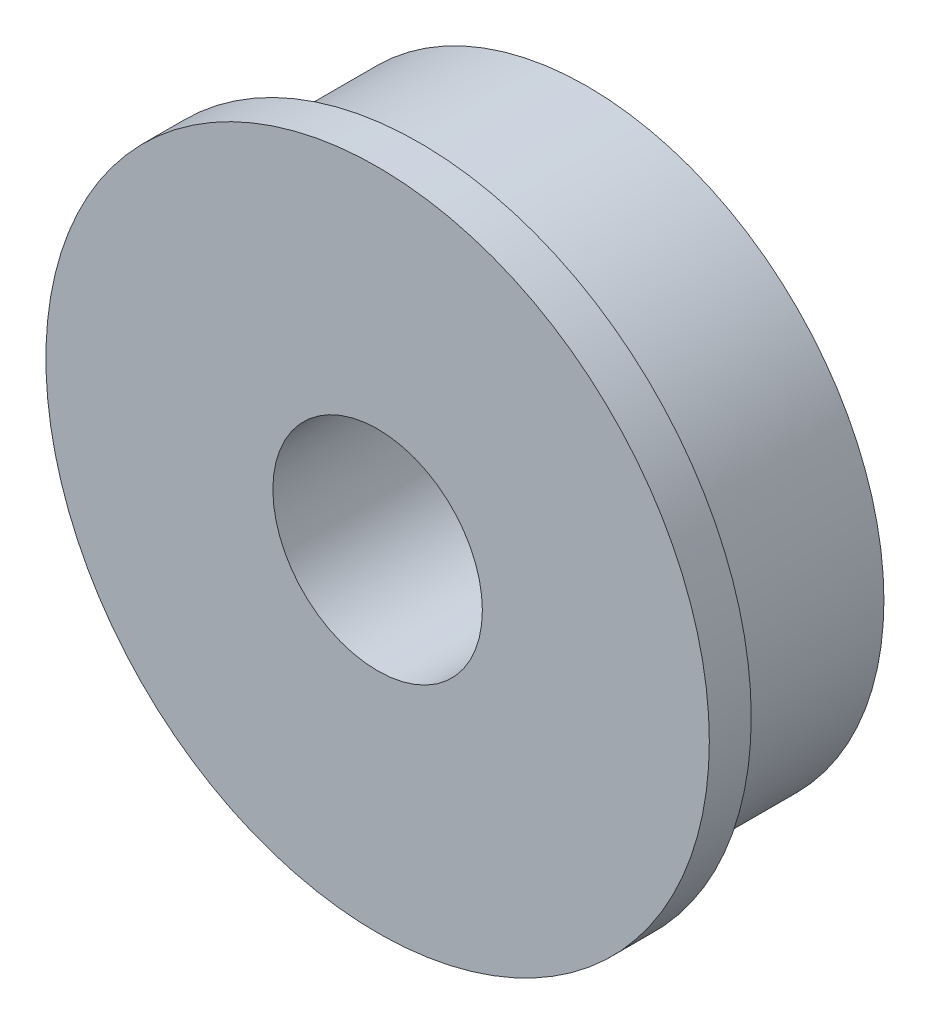
SolidWorks part; units mm, degrees
ref_plane "Płaszczyzna przednia" through (0, 0, 0) normal (0, 0, 1) x (1, 0, 0)
ref_plane "Płaszczyzna górna" through (0, 0, 0) normal (0, 1, 0) x (1, 0, 0)
ref_plane "Płaszczyzna prawa" through (0, 0, 0) normal (1, 0, 0) x (0, 0, -1)
sketch "Szkic1" plane through (0, 0, 0) normal (0, 0, 1) x (1, 0, 0)
  circle A0 centre (0, 0) radius 3
  circle A1 centre (0, 0) radius 8.5
  dimension "D1" = 17
  dimension "D2" = 6
extrude "Dodanie-wyciągnięcie1" add sketch "Szkic1" along normal blind 6
sketch "Szkic2" plane through (0, 0, 6) normal (0, 0, 1) x (1, 0, 0)
  circle A0 centre (0, 0) radius 8.5
  circle A1 centre (0, 0) radius 9.5
  dimension "D1" = 17
  dimension "D2" = 19
extrude "Dodanie-wyciągnięcie2" add sketch "Szkic2" against normal blind 1.2
